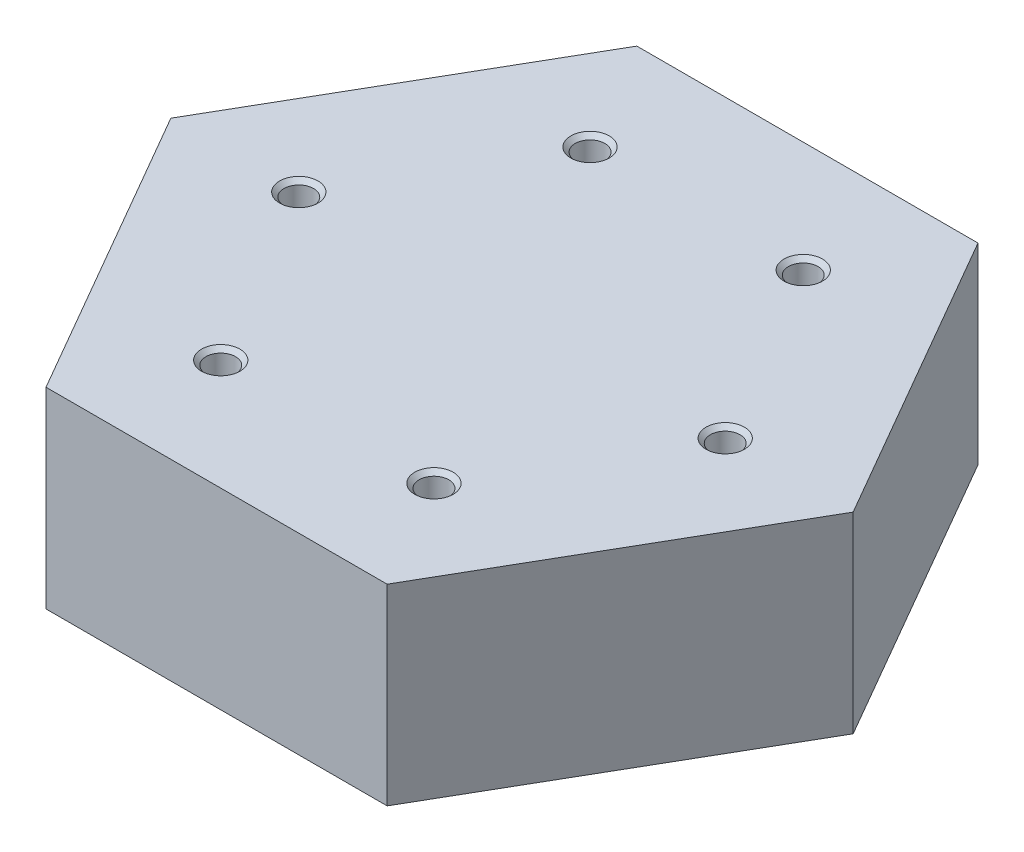
SolidWorks part; units mm, degrees
ref_plane "Front Plane" through (0, 0, 0) normal (0, 0, 1) x (1, 0, 0)
ref_plane "Top Plane" through (0, 0, 0) normal (0, 1, 0) x (1, 0, 0)
ref_plane "Right Plane" through (0, 0, 0) normal (1, 0, 0) x (0, 0, -1)
sketch "Sketch1" plane through (0, 0, 0) normal (0, 1, 0) x (1, 0, 0)
  line L0 (-58.6588, 0) -> (-29.3294, -50.8)
  line L1 (58.6588, 0) -> (29.3294, 50.8)
  line L2 (29.3294, 50.8) -> (-29.3294, 50.8)
  line L3 (-29.3294, 50.8) -> (-58.6588, 0)
  line L4 (-29.3294, -50.8) -> (29.3294, -50.8)
  line L5 (29.3294, -50.8) -> (58.6588, 0)
  circle A0 centre (0, 0) radius 50.8 construction
  dimension "D1" = 101.6
extrude "Boss-Extrude1" add sketch "Sketch1" along normal mid plane 33.02
sketch "Sketch3" plane through (0, 16.51, 0) normal (0, 1, 0) x (1, 0, 0)
  line L1 (18.3309, 31.75) -> (-18.3309, 31.75)
  line L2 (-18.3309, 31.75) -> (-36.6617, 0)
  line L3 (-36.6617, 0) -> (-18.3309, -31.75)
  line L4 (-18.3309, -31.75) -> (18.3309, -31.75)
  line L5 (18.3309, -31.75) -> (36.6617, 0)
  line L6 (36.6617, 0) -> (18.3309, 31.75)
  circle A0 centre (0, 0) radius 31.75 construction
  dimension "D1" = 63.5
hole_wizard "1/4-20 Tapped Hole1" positions "3DSketch1" profile "Sketch2" tap size "1/4-20" standard "ANSI Inch"
sketch3d "3DSketch1"
  line L0 (-29.3294, -16.51, -50.8) -> (-58.6588, 16.51, 0) construction
  line L2 (-58.6588, -16.51, 0) -> (-29.3294, 16.51, 50.8) construction
  point P4 (-43.9941, 0, -25.4)
  point P6 (-43.9941, 0, 25.4)
  point P22 (18.3309, 16.51, 31.75)
  point P25 (36.6617, 16.51, 0)
  point P32 (-18.3309, 16.51, -31.75)
  point P35 (-36.6617, 16.51, 0)
  point P38 (-18.3309, 16.51, 31.75)
  point P45 (18.3309, 16.51, -31.75)
cosmetic thread "Hole Thread1" parameters "D1"=12.7, "D2"=6.35
cosmetic thread "Hole Thread2" parameters "D1"=12.7, "D2"=6.35
cosmetic thread "Hole Thread3" parameters "D1"=12.7, "D2"=6.35
cosmetic thread "Hole Thread4" parameters "D1"=12.7, "D2"=6.35
sketch "Sketch2" plane through (-43.9941, 0, -25.4) normal (0, 1, 0) x (-0.5, 0, 0.866)
  line L0 (0, 0) -> (0, 20.5838)
  line L1 (0, 20.5838) -> (2.5527, 19.05)
  line L2 (2.5527, 19.05) -> (2.5527, 0.7493)
  line L3 (2.5527, 0.7493) -> (3.302, 0)
  line L5 (3.302, 0) -> (0, 0)
  line L6 (-2.5527, 0.7493) -> (-3.302, 0) construction
  line L10 (0, 20.5838) -> (-2.5527, 19.05) construction
  line L11 (0, -6.35) -> (0, 107.95) construction
  dimension "Tap Drill Dia." = 5.1054
  dimension "Tap Drill Depth" = 19.05
  dimension "Near C'Sink Dia." = 6.604
  dimension "Near C'Sink Angle" = 90
  dimension "Drill Angle" = 118
cosmetic thread "Hole Thread5" parameters "D1"=12.7, "D2"=6.35
cosmetic thread "Hole Thread6" parameters "D1"=12.7, "D2"=6.35
cosmetic thread "Hole Thread7" parameters "D1"=12.7, "D2"=6.35
cosmetic thread "Hole Thread8" parameters "D1"=12.7, "D2"=6.35
